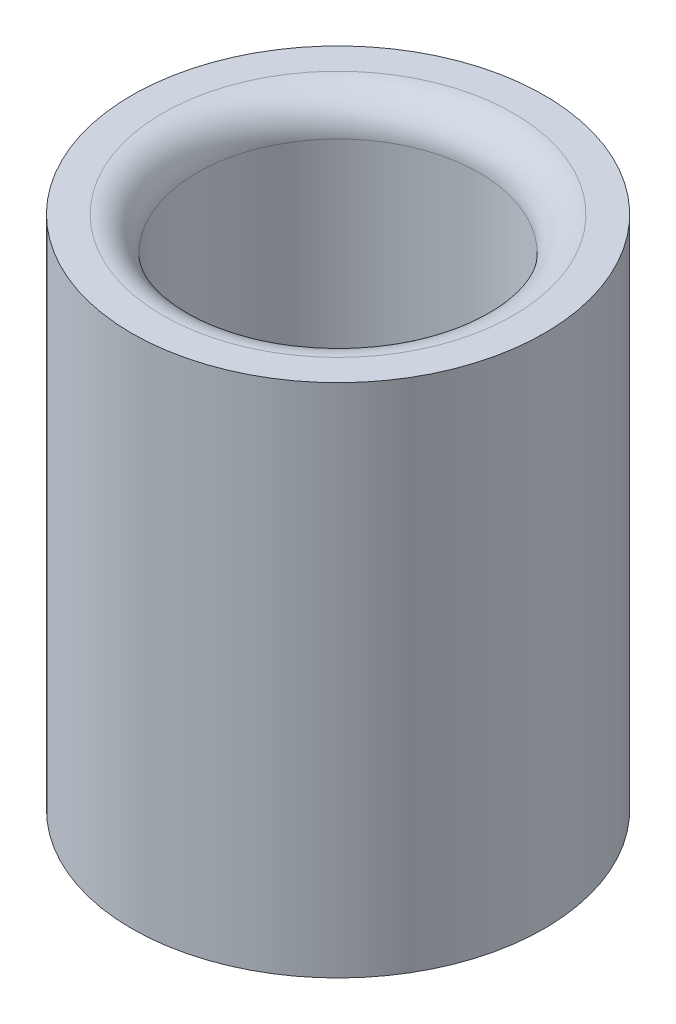
SolidWorks part; units mm, degrees
ref_plane "Alzado" through (0, 0, 0) normal (0, 0, 1) x (1, 0, 0)
ref_plane "Planta" through (0, 0, 0) normal (0, 1, 0) x (1, 0, 0)
ref_plane "Vista lateral" through (0, 0, 0) normal (1, 0, 0) x (0, 0, -1)
sketch "Croquis1" plane through (0, 0, 0) normal (0, 1, 0) x (1, 0, 0)
  circle A0 centre (0, 0) radius 6
  dimension "D1" = 12
extrude "Saliente-Extruir1" add sketch "Croquis1" along normal blind 15
sketch "Croquis2" plane through (0, 15, 0) normal (0, 1, 0) x (1, 0, 0)
  circle A0 centre (0, 0) radius 4.1
  dimension "D1" = 8.2
extrude "Cortar-Extruir1" cut sketch "Croquis2" against normal blind 9
fillet "Redondeo1" radius 1 1 edges at (0, 15, 4.1)
